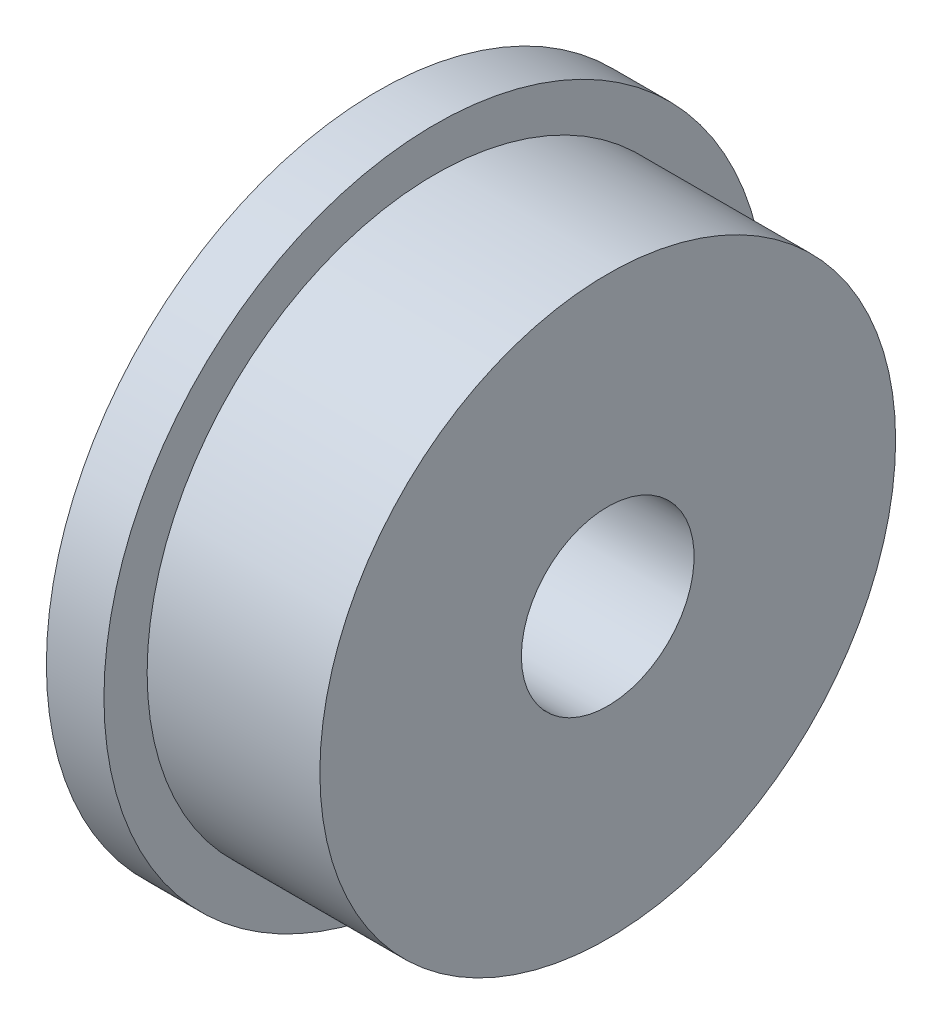
SolidWorks part; units mm, degrees
ref_plane "Front Plane" through (0, 0, 0) normal (0, 0, 1) x (1, 0, 0)
ref_plane "Top Plane" through (0, 0, 0) normal (0, 1, 0) x (1, 0, 0)
ref_plane "Right Plane" through (0, 0, 0) normal (1, 0, 0) x (0, 0, -1)
sketch "Sketch1" plane through (0, 0, 0) normal (0, 0, 1) x (1, 0, 0)
  line L0 (3.9873, 1.5) -> (3.9873, 5.75)
  line L1 (3.9873, 5.75) -> (4.9873, 5.75)
  line L2 (4.9873, 5.75) -> (4.9873, 5)
  line L3 (4.9873, 5) -> (7.9873, 5)
  line L4 (7.9873, 5) -> (7.9873, 1.5)
  line L5 (7.9873, 1.5) -> (3.9873, 1.5)
  line L6 (0, 0) -> (16.3584, 0) construction
  dimension "D1" = 5.75
  dimension "D2" = 5
  dimension "D3" = 4
  dimension "D4" = 1
  dimension "D5" = 1.5
revolve "Revolve1" add sketch "Sketch1" angle 360 about L6
